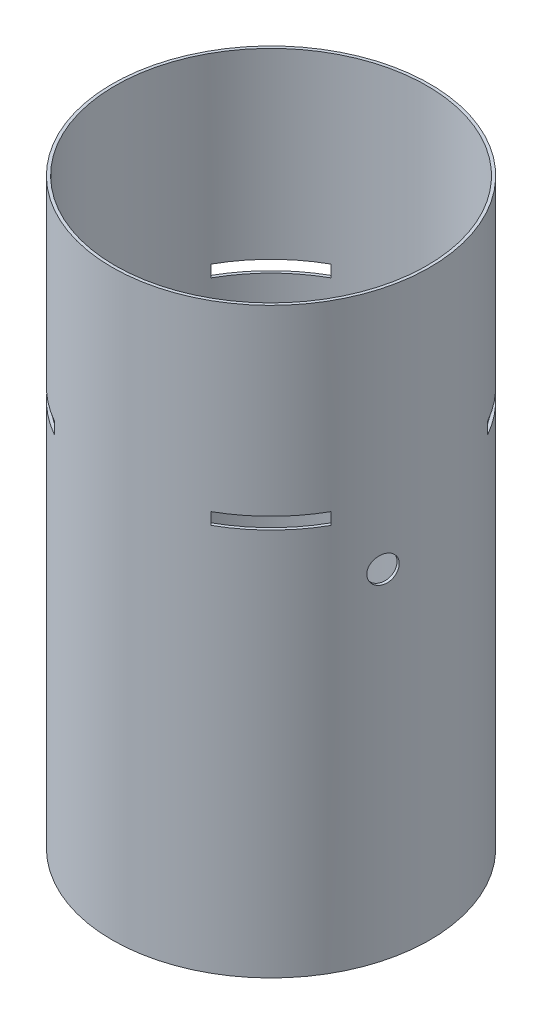
SolidWorks part; units mm, degrees
material "Thornel Mat VMA"
ref_plane "Front Plane" through (0, 0, 0) normal (0, 0, 1) x (1, 0, 0)
ref_plane "Top Plane" through (0, 0, 0) normal (0, 1, 0) x (1, 0, 0)
ref_plane "Right Plane" through (0, 0, 0) normal (1, 0, 0) x (0, 0, -1)
sketch "Sketch1" plane through (0, 0, 0) normal (0, 1, 0) x (1, 0, 0)
  circle A0 centre (0, 0) radius 74.7776
  circle A1 centre (0, 0) radius 76.2
  dimension "D1" = 149.5552
  dimension "D2" = 152.4
extrude "Boss-Extrude1" add sketch "Sketch1" along normal mid plane 279.4
ref_plane "Plane1" through (0, 0, 0) normal (0.7071, 0, -0.7071) x (-0.7071, 0, -0.7071)
sketch "Sketch2" plane through (0, 0, 0) normal (0.7071, 0, -0.7071) x (-0.7071, 0, -0.7071)
  line L0 (20.32, 52.07) -> (20.32, 46.355) construction
  line L1 (-20.32, 46.355) -> (-20.32, 52.07) construction
  line L2 (20.32, 46.355) -> (-20.32, 46.355) construction
  line L3 (-20.32, 52.07) -> (20.32, 52.07) construction
  line L4 (20.32, 52.07) -> (20.32, 46.355)
  line L5 (-20.32, 46.355) -> (-20.32, 52.07)
  line L6 (20.32, 46.355) -> (-20.32, 46.355)
  line L7 (-20.32, 52.07) -> (20.32, 52.07)
extrude "Cut-Extrude1" cut sketch "Sketch2" against normal through all
pattern_circular "CirPattern1" count 4 over 360 about axis through (0, 0, 0) along (0, 1, 0) of "Cut-Extrude1"
sketch "Sketch3" plane through (74.9775, 38.1, 20.0902) normal (0.9659, 0, 0.2588) x (0, -1, 0)
  circle A0 centre (15.24, 0) radius 6.35 construction
  circle A1 centre (15.24, 0) radius 6.35
extrude "Cut-Extrude2" cut sketch "Sketch3" against normal blind 6.35
equation "\"airframeInnerDiameter\"= 6in"
equation "\"outerDiameter\"= 6.112in"
equation "\"atsLength\"= 11in"
equation "\"atsInner\"= 5.888in"
equation "\"atsBand\"= 2in"
equation "\"atsCouplerOuter\"=\"airframeInnerDiameter\""
equation "\"atsOffsetFromAft\"= 3in"
equation "\"D1@Sketch1\"=\"atsInner\""
equation "\"D2@Sketch1\"=\"atsCouplerOuter\""
equation "\"D1@Boss-Extrude1\"=\"atsLength\""
